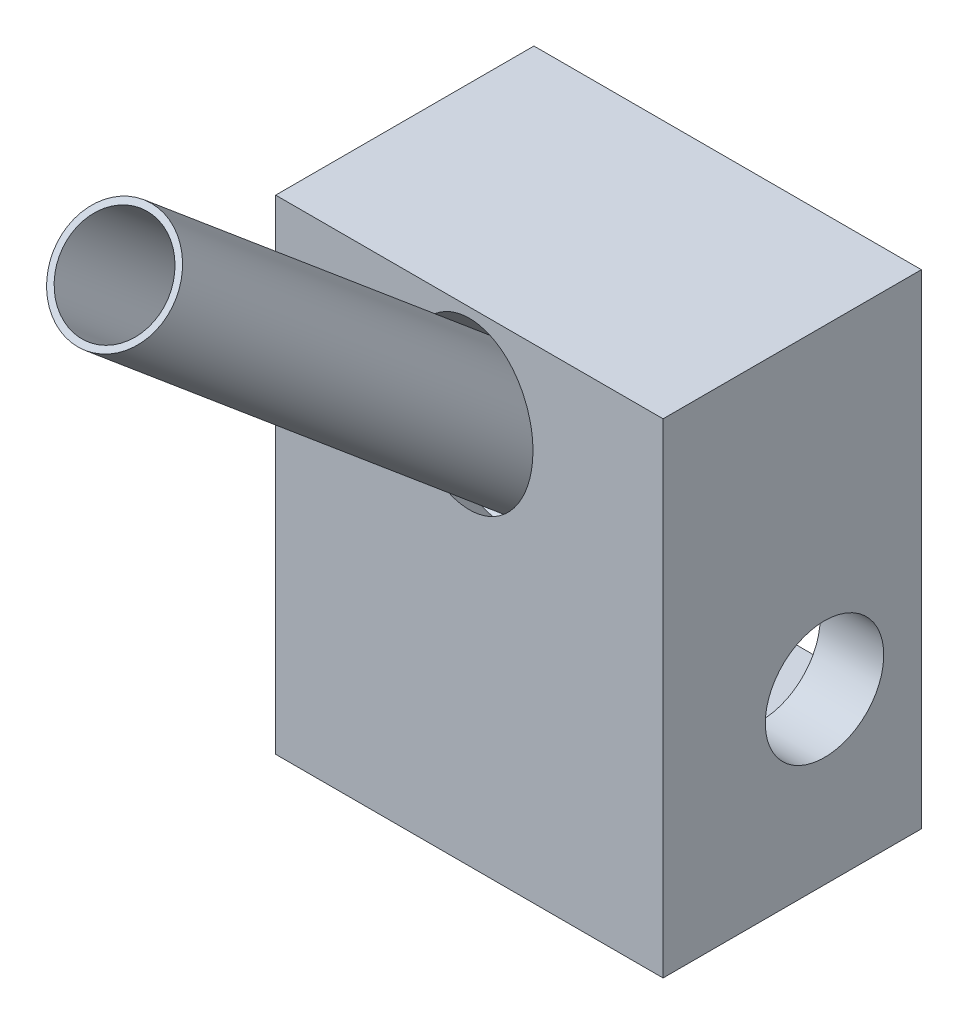
SolidWorks part; units mm, degrees
ref_plane "Front Plane" through (0, 0, 0) normal (0, 0, 1) x (1, 0, 0)
ref_plane "Top Plane" through (0, 0, 0) normal (0, 1, 0) x (1, 0, 0)
ref_plane "Right Plane" through (0, 0, 0) normal (1, 0, 0) x (0, 0, -1)
sketch "Sketch1" plane through (0, 0, 0) normal (0, 0, 1) x (1, 0, 0)
  line L1 (6066.2942, -5703.2258) -> (6096.7742, -5703.2258)
  line L2 (6066.2942, -5703.2258) -> (6066.2942, -5741.3258)
  line L3 (6066.2942, -5741.3258) -> (6096.7742, -5741.3258)
  line L4 (6096.7742, -5703.2258) -> (6096.7742, -5741.3258)
  dimension "D1" = 38.1
  dimension "D2" = 30.48
extrude "Boss-Extrude1" add sketch "Sketch1" along normal blind 20.32 from offset 7.5
sketch "Sketch2" plane through (0, 0, 7.5) normal (0, 0, -1) x (-1, 0, 0)
  line L0 (-6091.7742, -5710.8458) -> (-6096.7742, -5710.8458) construction
  line L1 (-6091.7742, -5710.8458) -> (-6071.3742, -5710.8458)
  line L2 (-6091.7742, -5710.8458) -> (-6091.7742, -5733.7058)
  line L3 (-6091.7742, -5733.7058) -> (-6071.3742, -5733.7058)
  line L4 (-6071.3742, -5710.8458) -> (-6071.3742, -5733.7058)
  line L5 (-6096.7742, -5741.3258) -> (-6096.7742, -5703.2258) construction
  line L6 (-6091.7742, -5710.8458) -> (-6091.7742, -5703.2258) construction
  line L7 (-6096.7742, -5703.2258) -> (-6066.2942, -5703.2258) construction
  line L8 (-6071.3742, -5710.8458) -> (-6066.2942, -5710.8458) construction
  line L9 (-6066.2942, -5703.2258) -> (-6066.2942, -5741.3258) construction
  line L10 (-6091.7742, -5733.7058) -> (-6091.7742, -5741.3258) construction
  line L11 (-6066.2942, -5741.3258) -> (-6096.7742, -5741.3258) construction
  dimension "D1" = 5
  dimension "D2" = 5.08
  dimension "D3" = 7.62
extrude "Cut-Extrude1" cut sketch "Sketch2" against normal blind 17.78
ref_plane "Plane3" through (0, -2342.7368, -2791.965) normal (0, -0.6428, -0.766) x (-1, 0, 0)
sketch "Sketch5" plane through (0, -2342.7368, -2791.965) normal (0, -0.6428, -0.766) x (-1, 0, 0)
  line L0 (-6081.5342, -4392.3948) -> (-6096.7742, -4392.3948) construction
  line L2 (-6081.5342, -4392.3948) -> (-6066.2942, -4392.3948) construction
  line L4 (-6066.2942, -4386.8068) -> (-6066.2942, -4415.9931) construction
  line L5 (-6096.7742, -4415.9931) -> (-6096.7742, -4386.8068) construction
  line L6 (-6081.5342, -4392.3948) -> (-6081.5342, -4386.8068) construction
  line L7 (-6096.7742, -4386.8068) -> (-6066.2942, -4386.8068) construction
  circle A0 centre (-6081.5342, -4392.3948) radius 5
  dimension "D1" = 10
  dimension "D2" = 5.588
extrude "Cut-Extrude2" cut sketch "Sketch5" along normal blind 23
sketch "Sketch10" plane through (0, -2342.7368, -2791.965) normal (0, -0.6428, -0.766) x (-1, 0, 0)
  line L0 (-6081.5342, -4392.3948) -> (-6096.7742, -4392.3948) construction
  line L2 (-6081.5342, -4392.3948) -> (-6066.2942, -4392.3948) construction
  circle A0 centre (-6081.5342, -4392.3948) radius 4.5
  circle A3 centre (-6081.5342, -4392.3948) radius 5 construction
  point P2 (-6084.5337, -4401.1393)
  dimension "D1" = 9
extrude "Boss-Extrude2" add sketch "Sketch10" against normal blind 31.75 and the other way blind 21.59 separate body
sketch "Sketch11" plane through (0, -2356.6146, -2808.5039) normal (0, -0.6428, -0.766) x (1, 0, 0)
  line L0 (6081.5342, 4387.8948) -> (6081.5342, 4392.3948) construction
  line L1 (6086.0342, 4392.3948) -> (6071.072, 4392.3948) construction
  circle A0 centre (6081.5342, 4392.3948) radius 4.5 construction
  circle A1 centre (6081.5342, 4392.3948) radius 4
  dimension "D1" = 8
extrude "Cut-Extrude6" cut sketch "Sketch11" against normal through all
hole_wizard "CSK for M3 Flat Head Machine Screw1" positions "Sketch13" profile "Sketch14" countersink size "M3" standard "ANSI Metric"
sketch "Sketch13" plane through (0, 0, 7.5) normal (0, 0, -1) x (-1, 0, 0)
  line L0 (-6061.5706, -5707.0749) -> (-6091.7776, -5707.1506) construction
  line L2 (-6091.7742, -5710.8458) -> (-6091.7776, -5707.1506) construction
  line L4 (-6091.7742, -5733.7058) -> (-6091.7742, -5737.401) construction
  line L6 (-6071.3742, -5733.7058) -> (-6071.7506, -5737.3818) construction
  circle A1 centre (-6059.8467, -5706.0609) radius 2 construction
  point P0 (-6091.7776, -5707.1506)
  point P2 (-6061.5706, -5707.0749)
  point P4 (-6071.7506, -5737.3818)
  point P6 (-6091.7742, -5737.401)
  point P13 (-6091.7776, -5707.1506)
sketch "Sketch14" plane through (6091.7776, -5707.1506, 7.5) normal (1, 0, 0) x (0, 1, 0)
  line L0 (0, 0) -> (0, 10)
  line L1 (0, 10) -> (1.7, 8.9785)
  line L2 (1.7, 8.9785) -> (1.7, 1.45)
  line L3 (1.7, 1.45) -> (3.15, 0)
  line L5 (3.15, 0) -> (0, 0)
  line L6 (-1.7, 1.45) -> (-3.15, 0) construction
  line L10 (0, 10) -> (-1.7, 8.9785) construction
  line L11 (0, -6.35) -> (0, 107.95) construction
  dimension "Hole Dia." = 3.4
  dimension "Hole Depth" = 10
  dimension "Near C'Sink Dia." = 6.3
  dimension "Near C'Sink Angle" = 90
  dimension "Drill Angle" = 118
sketch "Sketch17" plane through (6096.7742, 0, 0) normal (1, 0, 0) x (0, 0, -1)
  line L0 (-7.5, -5741.3258) -> (-7.5, -5703.2258) construction
  circle A0 centre (-15.12, -5727.9927) radius 4.6596
  point P4 (-20.2, -5732.6203)
  point P5 (-20.2, -5732.8856)
  point P6 (-20.2, -5733.104)
  point P7 (-20.2, -5732.89)
  point P8 (-20.2, -5733.0925)
  point P9 (-15.12, -5727.9927)
  dimension "D1" = 7.62
extrude "Cut-Extrude7" cut sketch "Sketch17" against normal through all
sketch "Sketch18" plane through (0, 0, 25.28) normal (0, 0, -1) x (-1, 0, 0)
  line L0 (-6081.5742, -5733.7058) -> (-6081.5742, -5722.6783) construction
  line L1 (-6091.7742, -5733.7058) -> (-6071.3742, -5733.7058) construction
  line L2 (-6091.7742, -5722.2758) -> (-6081.5742, -5728.192) construction
  line L3 (-6091.7742, -5710.8458) -> (-6091.7742, -5733.7058) construction
  line L5 (-6090.1827, -5715.9183) -> (-6072.9657, -5715.9183)
  line L6 (-6090.1827, -5715.9183) -> (-6090.1827, -5740.4658)
  line L7 (-6090.1827, -5740.4658) -> (-6072.9657, -5740.4658)
  line L8 (-6072.9657, -5715.9183) -> (-6072.9657, -5740.4658)
  line L9 (-6090.1827, -5715.9183) -> (-6072.9657, -5740.4658) construction
  line L10 (-6090.1827, -5740.4658) -> (-6072.9657, -5715.9183) construction
  point P12 (-6068.1657, -5740.4658)
